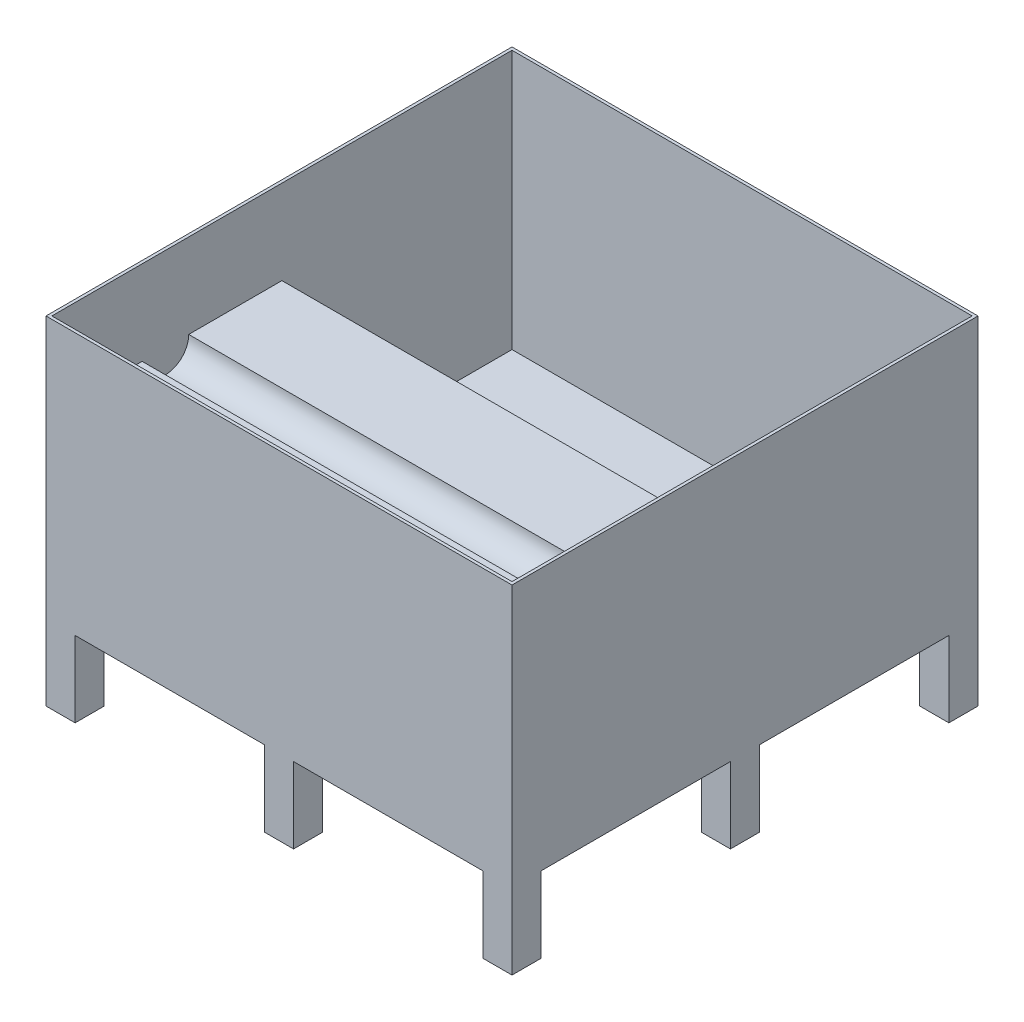
SolidWorks part; units mm, degrees
ref_plane "Front Plane" through (0, 0, 0) normal (0, 0, 1) x (1, 0, 0)
ref_plane "Top Plane" through (0, 0, 0) normal (0, 1, 0) x (1, 0, 0)
ref_plane "Right Plane" through (0, 0, 0) normal (1, 0, 0) x (0, 0, -1)
sketch "Sketch1" plane through (0, 0, 0) normal (0, 1, 0) x (1, 0, 0)
  line L1 (0, 0) -> (800, 0)
  line L2 (0, 0) -> (0, -800)
  line L3 (0, -800) -> (800, -800)
  line L4 (800, 0) -> (800, -800)
  dimension "D1" = 800
  dimension "D2" = 800
extrude "Boss-Extrude1" add sketch "Sketch1" along normal blind 450
shell "Shell1" thickness 5
sketch "Sketch2" plane through (0, 5, 0) normal (0, 1, 0) x (1, 0, 0)
  line L0 (5, -5) -> (5, -795) construction
  line L1 (5, -795) -> (795, -795)
  line L2 (5, -795) -> (5, -5)
  line L3 (5, -5) -> (795, -5)
  line L4 (795, -795) -> (795, -5)
  line L5 (5, -795) -> (795, -795) construction
  line L6 (5, -400) -> (795, -400)
  line M6 (5, -795) -> (795, -795)
  line M7 (795, -795) -> (795, -5)
extrude "Boss-Extrude2" add sketch "Sketch2" along normal blind 300 contours L6 L2 M6 M7
sketch "Sketch3" plane through (800, 0, 0) normal (1, 0, 0) x (0, 0, -1)
  line L0 (-800, 305) -> (0, 305) construction
  line L1 (-800, 450) -> (-800, 0) construction
  line L2 (0, 450) -> (0, 0) construction
  line L4 (-800, 450) -> (0, 450) construction
  circle A0 centre (-600, 305) radius 40
  point P10 (0, 0)
  dimension "D2" = 80
  dimension "D1" = 145
  dimension "D3" = 200
extrude "Cut-Extrude1" cut sketch "Sketch3" against normal up to surface (790 mm away) from offset 5 up to face at (5, 253.3333, 400) offset against normal yes
sketch "Sketch4" plane through (0, 0, 0) normal (0, -1, 0) x (1, 0, 0)
  line L1 (0, 800) -> (50, 800)
  line L2 (0, 800) -> (0, 750)
  line L3 (0, 750) -> (50, 750)
  line L4 (50, 800) -> (50, 750)
  line L32 (375, 800) -> (375, 750)
  line L33 (375, 800) -> (425, 800)
  line L34 (425, 800) -> (425, 750)
  line L35 (375, 750) -> (425, 750)
  line L36 (750, 800) -> (750, 750)
  line L37 (750, 800) -> (800, 800)
  line L38 (800, 800) -> (800, 750)
  line L39 (750, 750) -> (800, 750)
  line L40 (375, 425) -> (375, 375)
  line L41 (375, 425) -> (425, 425)
  line L42 (425, 425) -> (425, 375)
  line L43 (375, 375) -> (425, 375)
  line L44 (750, 425) -> (750, 375)
  line L45 (750, 425) -> (800, 425)
  line L46 (800, 425) -> (800, 375)
  line L47 (750, 375) -> (800, 375)
  line L48 (375, 50) -> (375, 0)
  line L49 (375, 50) -> (425, 50)
  line L50 (425, 50) -> (425, 0)
  line L51 (375, 0) -> (425, 0)
  line L52 (750, 50) -> (750, 0)
  line L53 (750, 50) -> (800, 50)
  line L54 (800, 50) -> (800, 0)
  line L55 (750, 0) -> (800, 0)
  line L56 (0, 425) -> (0, 375)
  line L57 (0, 425) -> (50, 425)
  line L58 (50, 425) -> (50, 375)
  line L59 (0, 375) -> (50, 375)
  line L60 (0, 50) -> (0, 0)
  line L61 (0, 50) -> (50, 50)
  line L62 (50, 50) -> (50, 0)
  line L63 (0, 0) -> (50, 0)
  dimension "D1" = 50
  dimension "D2" = 50
  dimension "D3" = 3
  dimension "D4" = 3
extrude "Boss-Extrude3" add sketch "Sketch4" along normal blind 130
